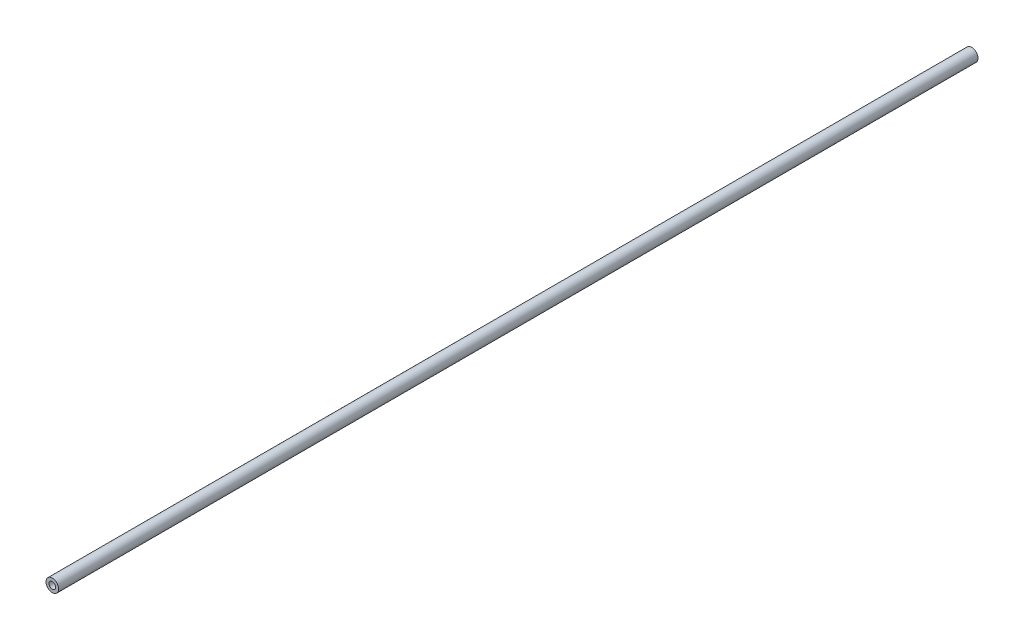
SolidWorks part; units mm, degrees
material "6061-T6 (SS)"
ref_plane "Front Plane" through (0, 0, 0) normal (0, 0, 1) x (1, 0, 0)
ref_plane "Top Plane" through (0, 0, 0) normal (0, 1, 0) x (1, 0, 0)
ref_plane "Right Plane" through (0, 0, 0) normal (1, 0, 0) x (0, 0, -1)
sketch "Sketch1" plane through (0, 0, 0) normal (0, 0, 1) x (1, 0, 0)
  circle A0 centre (0, 0) radius 4.7625
  circle A1 centre (0, 0) radius 2.4892
  dimension "D1" = 4.9784
  dimension "D2" = 9.525
extrude "Boss-Extrude1" add sketch "Sketch1" along normal blind 692.15
